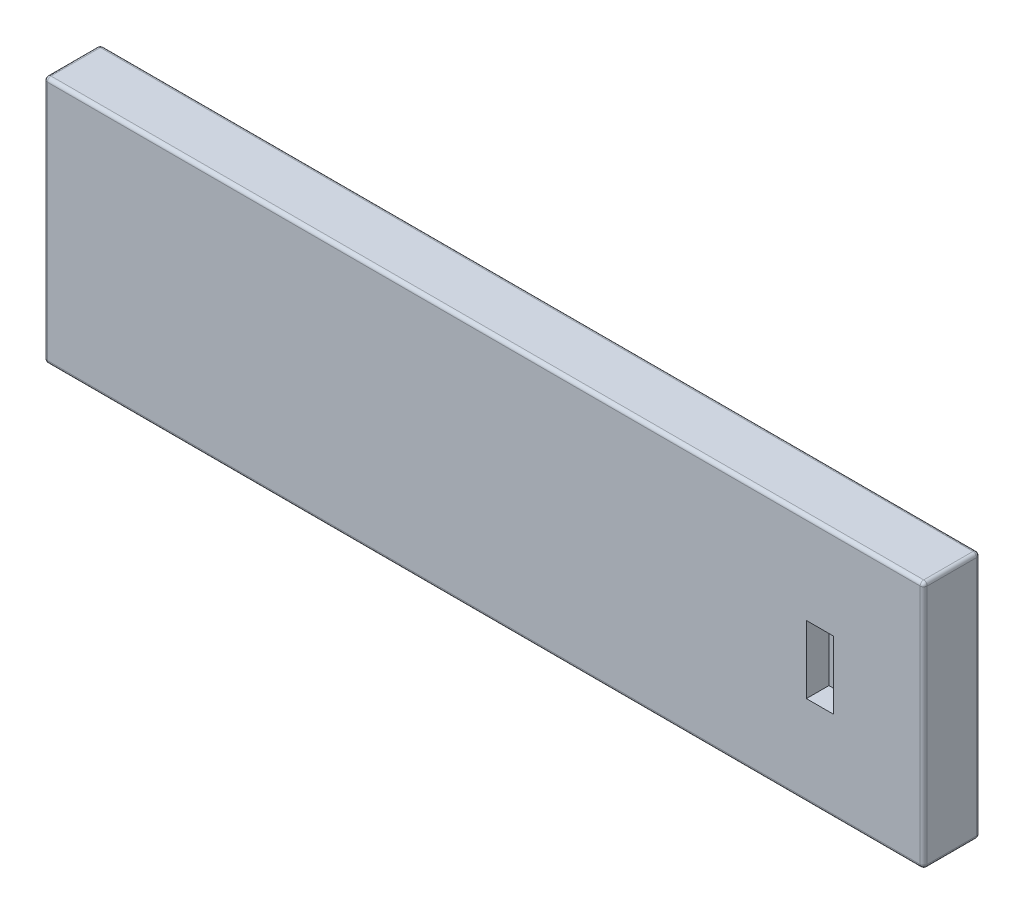
SolidWorks part; units mm, degrees
other "Defeature"
ref_plane "Front Plane" through (0, 0, 0) normal (0, 0, 1) x (1, 0, 0)
ref_plane "Top Plane" through (0, 0, 0) normal (0, 1, 0) x (1, 0, 0)
ref_plane "Right Plane" through (0, 0, 0) normal (1, 0, 0) x (0, 0, -1)
sketch "Sketch1" plane through (0, 0, 0) normal (0, 0, 1) x (1, 0, 0)
  line L1 (-61.9125, 17.4625) -> (61.9125, 17.4625)
  line L2 (-61.9125, 17.4625) -> (-61.9125, -17.4625)
  line L3 (-61.9125, -17.4625) -> (61.9125, -17.4625)
  line L4 (61.9125, 17.4625) -> (61.9125, -17.4625)
  line L5 (-61.9125, 17.4625) -> (61.9125, -17.4625) construction
  line L6 (-61.9125, -17.4625) -> (61.9125, 17.4625) construction
  point P0 (0, 0)
  dimension "D1" = 123.825
  dimension "D2" = 34.925
extrude "Boss-Extrude1" add sketch "Sketch1" along normal mid plane 7.9375
sketch "Sketch2" plane through (0, 0, 3.9688) normal (0, 0, 1) x (1, 0, 0)
  line L0 (0, 0) -> (61.9125, 0) construction
  line L1 (61.9125, -17.4625) -> (61.9125, 17.4625) construction
  line L3 (45.4025, 4.7625) -> (49.2125, 4.7625)
  line L4 (45.4025, 4.7625) -> (45.4025, -4.7625)
  line L5 (45.4025, -4.7625) -> (49.2125, -4.7625)
  line L6 (49.2125, 4.7625) -> (49.2125, -4.7625)
  line L7 (45.4025, 4.7625) -> (49.2125, -4.7625) construction
  line L8 (45.4025, -4.7625) -> (49.2125, 4.7625) construction
  point P5 (47.3075, 0)
  dimension "D1" = 3.81
  dimension "D2" = 9.525
  dimension "D3" = 12.7
extrude "Cut-Extrude1" cut sketch "Sketch2" against normal blind 3.175
fillet "Fillet2" radius 0.5 8 edges at (61.9125, -17.4625, 0) (61.9125, 17.4625, 0) (-61.9125, -17.4625, 0) (-61.9125, 17.4625, 0) (-61.9125, 0, 3.9688) (0, -17.4625, 3.9688) (61.9125, 0, 3.9688) (0, 17.4625, 3.9688)
fillet "Fillet3" radius 0.5 8 edges at (61.7661, 17.3161, -3.9688) (0, 17.4625, -3.9688) (-61.7661, 17.3161, -3.9688) (-61.9125, 0, -3.9688) (-61.7661, -17.3161, -3.9688) (0, -17.4625, -3.9688) (61.7661, -17.3161, -3.9688) (61.9125, 0, -3.9688)
sketch "Sketch3" plane through (-61.9125, 0, 0) normal (-1, 0, 0) x (0, 0, 1)
  line L0 (-0.9753, 16.9625) -> (-0.9753, -16.9625) construction
  line L1 (3.4688, 16.9625) -> (-3.4687, 16.9625) construction
  line L2 (-3.4687, -16.9625) -> (3.4688, -16.9625) construction
  text T0 "E4 - 510 | JCIII" font "Century Gothic" height 2
extrude "Cut-Extrude2" cut sketch "Sketch3" against normal blind 1
equation "\"BattWidth\"= 4 + 14 / 16"
equation "\"BattHeight\"= 1 + 3 / 8"
equation "\"BattDepth\"= 5 / 16"
equation "\"D1@Sketch1\"=\"BattWidth\""
equation "\"D2@Sketch1\"=\"BattHeight\""
equation "\"D1@Boss-Extrude1\"=\"BattDepth\""
